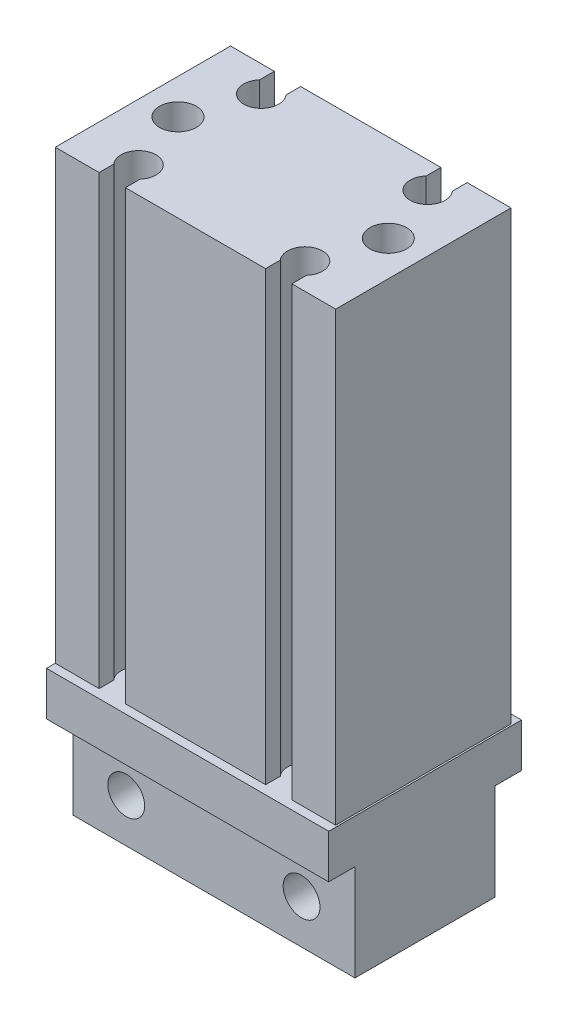
SolidWorks part; units mm, degrees
ref_plane "前视基准面" through (0, 0, 0) normal (0, 0, 1) x (1, 0, 0)
ref_plane "上视基准面" through (0, 0, 0) normal (0, 1, 0) x (1, 0, 0)
ref_plane "右视基准面" through (0, 0, 0) normal (1, 0, 0) x (0, 0, -1)
sketch "草图1" plane through (0, 0, 0) normal (0, 1, 0) x (1, 0, 0)
  line L0 (0, 0) -> (0, 11.2243) construction
  line L1 (-16, -10) -> (-11, -10)
  line L2 (-16, -10) -> (-16, 10)
  line L3 (-16, 10) -> (-11, 10)
  line L4 (16, -10) -> (16, 10)
  line L5 (-16, -10) -> (16, 10) construction
  line L6 (-16, 10) -> (16, -10) construction
  line L7 (0, 0) -> (10.6409, 0) construction
  line L9 (-8, 8.3229) -> (-8, 10)
  line L10 (-11, 8.3229) -> (-11, 10)
  line L14 (11, 8.3229) -> (11, 10)
  line L17 (-11, -8.3229) -> (-11, -10)
  line L18 (8, -8.3229) -> (8, -10)
  line L19 (8, 8.3229) -> (8, 10)
  line L20 (-8, -8.3229) -> (-8, -10)
  line L21 (11, -8.3229) -> (11, -10)
  line L22 (11, -10) -> (16, -10)
  line L27 (11, 10) -> (16, 10)
  line L28 (-8, 10) -> (8, 10)
  line L29 (-8, -10) -> (8, -10)
  arc A0 (-11, 8.3229) -> (-8, 8.3229) centre (-9.5, 7) ccw
  arc A1 (8, 8.3229) -> (11, 8.3229) centre (9.5, 7) ccw
  arc A2 (8, -8.3229) -> (11, -8.3229) centre (9.5, -7) cw
  arc A3 (-11, -8.3229) -> (-8, -8.3229) centre (-9.5, -7) cw
  point P0 (0, 0)
  point P17 (-8, 7)
  point P19 (-8, 12.5017)
  point P20 (-11, 7)
  point P21 (-11, 12.5017)
  point P24 (-9.5, -11.024)
  point P28 (11, 7)
  point P29 (11, 11.2243)
  point P30 (-11, -7)
  point P31 (-11, -11.024)
  point P32 (8, -7)
  point P33 (8, -11.3535)
  point P34 (8, 7)
  point P35 (8, 11.2243)
  point P36 (-8, -7)
  point P37 (-8, -11.024)
  point P38 (11, -7)
  point P39 (11, -11.3535)
  dimension "D3" = 4
  dimension "D5" = 4
  dimension "D6" = 3
  dimension "D7" = 19
  dimension "D1" = 32
  dimension "D2" = 20
  dimension "D4" = 3
  dimension "D8" = 9.5
extrude "拉伸1" add sketch "草图1" along normal blind 51
sketch "草图4" plane through (-16, 0, 0) normal (-1, 0, 0) x (0, 0, 1)
  line L0 (-11, 0) -> (-11, -5)
  line L1 (-11, -5) -> (-8, -5)
  line L2 (-8, -5) -> (-8, -16)
  line L3 (-8, -16) -> (8, -16)
  line L4 (8, -16) -> (8, -5)
  line L5 (8, -5) -> (11, -5)
  line L6 (11, -5) -> (11, 0)
  line L8 (10, 51) -> (10, 0) construction
  line L9 (-11, 0) -> (11, 0)
  dimension "D1" = 22
  dimension "D2" = 16
  dimension "D3" = 3
  dimension "D4" = 1
  dimension "D5" = 5
  dimension "D6" = 5
  dimension "D7" = 16
extrude "拉伸2" add sketch "草图4" against normal blind 32.2 separate body
sketch "草图5" plane through (0, -16, 0) normal (0, -1, 0) x (1, 0, 0)
  circle A0 centre (0, 0) radius 7
  dimension "D1" = 14
extrude "拉伸3" cut sketch "草图5" against normal blind 4
sketch "草图7" plane through (0, -16, 0) normal (0, -1, 0) x (1, 0, 0)
  line L2 (0, 0) -> (0, 16.7895) construction
  circle A1 centre (-10, 0) radius 1.5
  circle A2 centre (10, 0) radius 1.5
  dimension "D3" = 3
extrude "拉伸4" cut sketch "草图7" against normal blind 8
sketch "草图8" plane through (0, -12, 0) normal (0, -1, 0) x (1, 0, 0)
  circle A0 centre (0, 0) radius 2.5
  dimension "D1" = 5
extrude "拉伸5" cut sketch "草图8" against normal blind 50
sketch "草图9" plane through (0, 0, 8) normal (0, 0, 1) x (1, 0, 0)
  circle A0 centre (10.1, -11) radius 2.1
  circle A1 centre (-9.9, -11) radius 2.1
  dimension "D1" = 4.2
  dimension "D2" = 4.2
extrude "拉伸6" cut sketch "草图9" against normal through all
sketch "草图10" plane through (0, 51, 0) normal (0, 1, 0) x (1, 0, 0)
  line L0 (0, 0) -> (0, 7.0814) construction
  circle A0 centre (12, 0) radius 2.1
  circle A1 centre (-12, 0) radius 2.1
  dimension "D1" = 4.2
  dimension "D2" = 4.2
  dimension "D3" = 24
extrude "拉伸7" cut sketch "草图10" against normal blind 12
sketch "草图11" plane through (-16, 0, 0) normal (-1, 0, 0) x (0, 0, 1)
  line L0 (-10, 51) -> (10, 51) construction
  circle A0 centre (0, 38.5) radius 2.1
  circle A1 centre (0, 12.5) radius 2.1
  dimension "D1" = 4.2
  dimension "D2" = 4.2
  dimension "D3" = 26
  dimension "D4" = 12.5
extrude "拉伸8" cut sketch "草图11" against normal blind 6
